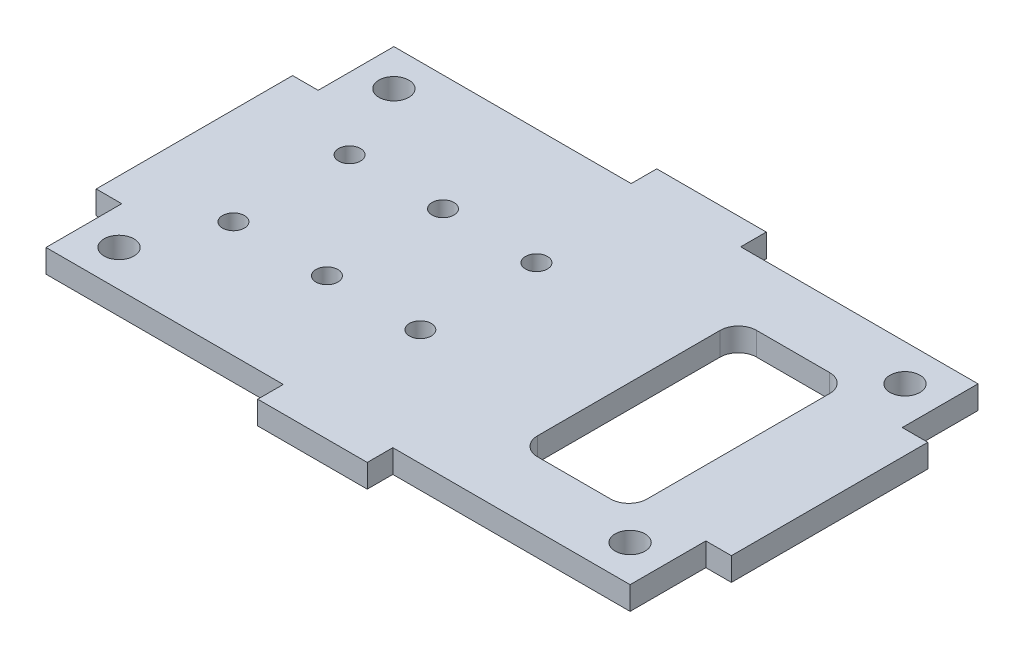
SolidWorks part; units mm, degrees
ref_plane "Front Plane" through (0, 0, 0) normal (0, 0, 1) x (1, 0, 0)
ref_plane "Top Plane" through (0, 0, 0) normal (0, 1, 0) x (1, 0, 0)
ref_plane "Right Plane" through (0, 0, 0) normal (1, 0, 0) x (0, 0, -1)
sketch "Sketch2" plane through (0, 0, 0) normal (0, 1, 0) x (1, 0, 0)
  line L0 (0, -1.7463) -> (0, 1.7463) construction
  line L1 (-40, 23.825) -> (40, 23.825)
  line L2 (-40, 23.825) -> (-40, -23.825)
  line L3 (-40, -23.825) -> (40, -23.825)
  line L4 (40, 23.825) -> (40, -23.825)
  point P4 (0, -23.825)
  dimension "D1 " = 47.65
  dimension "D2" = 80
  dimension "D4" = 23.825
extrude "Boss-Extrude1" add sketch "Sketch2" along normal blind 3.175
sketch "Sketch3" plane through (0, 3.175, 0) normal (0, 1, 0) x (1, 0, 0)
  line L0 (40, 23.825) -> (-40, 23.825) construction
  line L1 (-7.5, 23.825) -> (7.5, 23.825)
  line L2 (-7.5, 23.825) -> (-7.5, 27.325)
  line L3 (-7.5, 27.325) -> (7.5, 27.325)
  line L4 (7.5, 23.825) -> (7.5, 27.325)
  point P6 (0, 23.825)
  dimension "D1" = 15
  dimension "D2" = 3.5
  dimension "D3" = 0
extrude "Boss-Extrude2" add sketch "Sketch3" against normal blind 3.175
sketch "Sketch4" plane through (0, 3.175, 0) normal (0, 1, 0) x (1, 0, 0)
  line L0 (-40, 23.825) -> (-40, -23.825) construction
  line L1 (-40, 13.45) -> (-43.5, 13.45)
  line L2 (-40, 13.45) -> (-40, -13.45)
  line L3 (-40, -13.45) -> (-43.5, -13.45)
  line L4 (-43.5, 13.45) -> (-43.5, -13.45)
  point P6 (-40, 0)
  dimension "D1" = 26.9
  dimension "D2" = 3.5
extrude "Boss-Extrude3" add sketch "Sketch4" against normal blind 3.175
mirror "Mirror1" about plane through (0, 0, 0) normal (1, 0, 0) of "Boss-Extrude3"
mirror "Mirror2" about plane through (0, 0, 0) normal (0, 0, 1) of "Boss-Extrude2"
sketch "Sketch5" plane through (0, 3.175, 0) normal (0, 1, 0) x (1, 0, 0)
  line L0 (-1.7463, 0) -> (1.7463, 0) construction
  line L1 (-40, 23.825) -> (-40, 13.45) construction
  circle A0 centre (-30.2, 7.95) radius 1.5
  dimension "D2" = 3
  dimension "D3" = 9.8
  dimension "D1" = 7.95
extrude "Cut-Extrude1" cut sketch "Sketch5" against normal blind 20
pattern_linear "LPattern1" count 3 spacing 12.8 along (1, 0, 0) of "Cut-Extrude1"
mirror "Mirror3" about plane through (0, 0, 0) normal (0, 0, 1) of "LPattern1", "Cut-Extrude1"
sketch "Sketch6" plane through (0, 3.175, 0) normal (0, 1, 0) x (1, 0, 0)
  line L1 (16, 15) -> (31, 15)
  line L2 (16, 15) -> (16, -15)
  line L3 (16, -15) -> (31, -15)
  line L4 (31, 15) -> (31, -15)
  point P4 (31, 0)
  dimension "D1" = 30
  dimension "D2" = 15
  dimension "D3" = 0
  dimension "D4" = 16
extrude "Cut-Extrude2" cut sketch "Sketch6" against normal through all
fillet "Fillet1" radius 2.5 4 edges at (31, 1.5875, 15) (16, 1.5875, 15) (31, 1.5875, -15) (16, 1.5875, -15)
sketch "Sketch7" plane through (0, 3.175, 0) normal (0, 1, 0) x (1, 0, 0)
  line L0 (-7.5, 23.825) -> (-40, 23.825) construction
  line L1 (-40, 23.825) -> (-40, 13.45) construction
  line L2 (0, -1.7463) -> (0, 1.7463) construction
  line L3 (-1.7463, 0) -> (1.7463, 0) construction
  circle A0 centre (-35, 18.825) radius 2.05
  circle A1 centre (35, 18.825) radius 2.05
  circle A2 centre (-35, -18.825) radius 2.05
  circle A3 centre (35, -18.825) radius 2.05
  dimension "D1" = 4.1
  dimension "D2" = 5
  dimension "D3" = 5
extrude "Cut-Extrude3" cut sketch "Sketch7" against normal through all both and the other way through all
